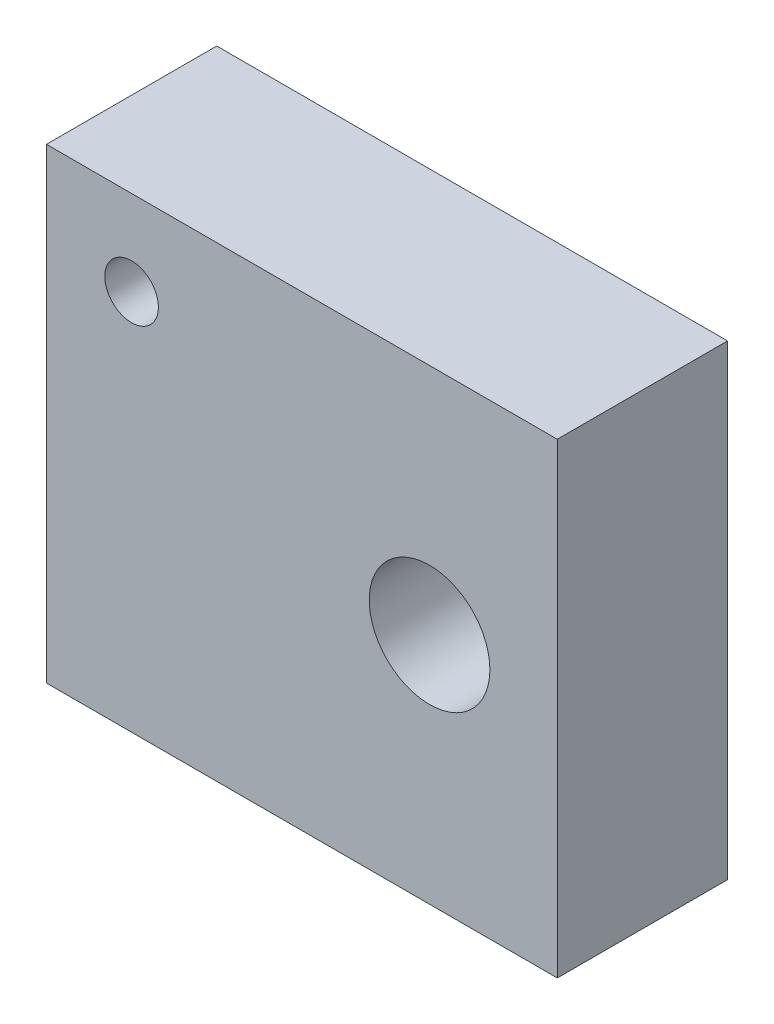
SolidWorks part; units mm, degrees
material "Balsa"
ref_plane "Front Plane" through (0, 0, 0) normal (0, 0, 1) x (1, 0, 0)
ref_plane "Top Plane" through (0, 0, 0) normal (0, 1, 0) x (1, 0, 0)
ref_plane "Right Plane" through (0, 0, 0) normal (1, 0, 0) x (0, 0, -1)
sketch "Sketch1" plane through (0, 0, 0) normal (0, 0, 1) x (1, 0, 0)
  line L1 (0, 0) -> (19.05, 0)
  line L2 (0, 0) -> (0, 17.4)
  line L3 (0, 17.4) -> (19.05, 17.4)
  line L4 (19.05, 0) -> (19.05, 17.4)
  dimension "D1" = 19.05
  dimension "D2" = 17.4
extrude "Boss-Extrude1" add sketch "Sketch1" along normal blind 6.35
hole_wizard "M4 Clearance Hole1" positions "Sketch3" profile "Sketch2" hole size "M4" standard "Ansi Metric"
sketch "Sketch3" plane through (0, 0, 6.35) normal (0, 0, 1) x (1, 0, 0)
  line L0 (14.2875, 17.4) -> (14.2875, 0) construction
  line L1 (19.05, 17.4) -> (0, 17.4) construction
  line L2 (0, 0) -> (19.05, 0) construction
  line L4 (19.05, 0) -> (19.05, 17.4) construction
  point P0 (14.2875, 8.7)
  dimension "D1" = 4.7625
sketch "Sketch2" plane through (14.2875, 8.7, 6.35) normal (1, 0, 0) x (0, -1, 0)
  line L0 (0, 0) -> (0, 14.0519)
  line L1 (0, 14.0519) -> (2.25, 12.7)
  line L2 (2.25, 12.7) -> (2.25, 0)
  line L5 (2.25, 0) -> (0, 0)
  line L10 (0, 14.0519) -> (-2.25, 12.7) construction
  line L11 (0, -6.35) -> (0, 107.95) construction
  dimension "Hole Dia." = 4.5
  dimension "Hole Depth" = 12.7
  dimension "Drill Angle" = 118
sketch "Sketch4" plane through (0, 0, 6.35) normal (0, 0, 1) x (1, 0, 0)
  line L0 (3.175, 14.225) -> (0, 14.225) construction
  line L2 (19.05, 17.4) -> (0, 17.4) construction
  circle A0 centre (3.175, 14.225) radius 1
  dimension "D2" = 2
  dimension "D1" = 3.175
  dimension "D3" = 3.175
extrude "Cut-Extrude1" cut sketch "Sketch4" against normal through all
